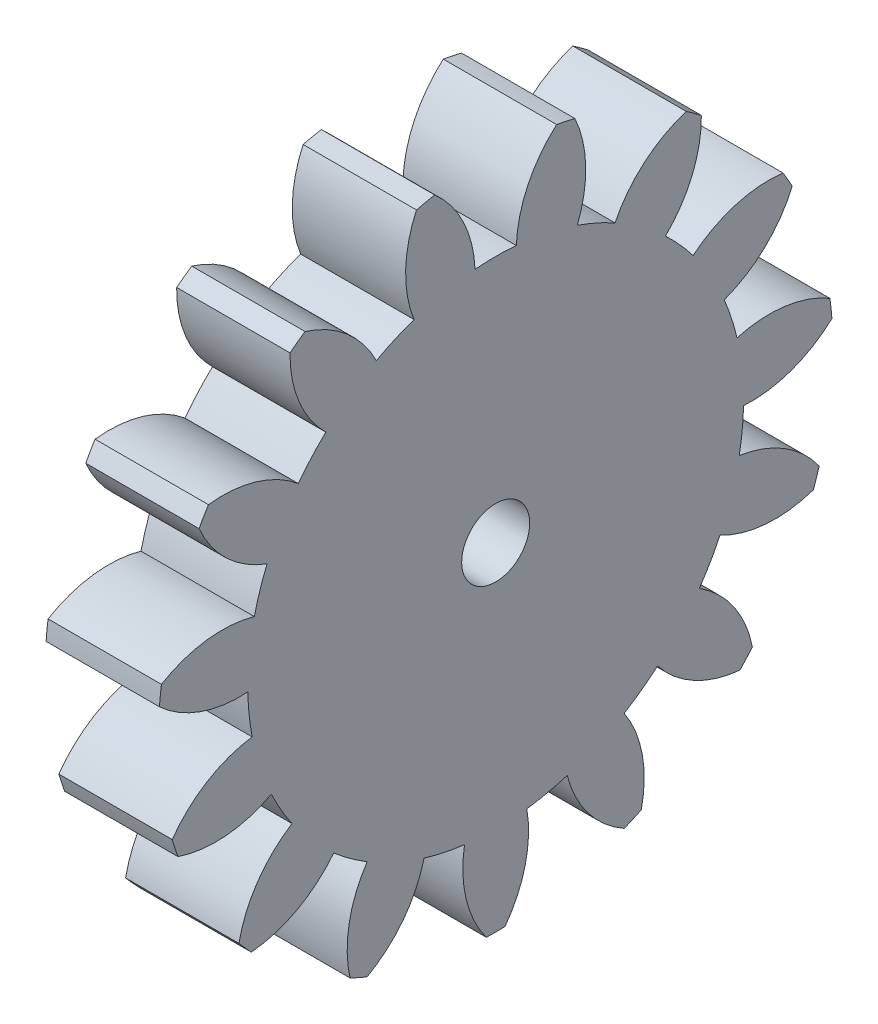
SolidWorks part; units mm, degrees
ref_plane "Plane1" through (0, 0, 0) normal (0, 0, 1) x (1, 0, 0)
ref_plane "Plane2" through (0, 0, 0) normal (0, 1, 0) x (1, 0, 0)
ref_plane "Plane3" through (0, 0, 0) normal (1, 0, 0) x (0, 0, -1)
sketch "HoldingSke" plane through (0, 0, 0) normal (0, 1, 0) x (1, 0, 0)
  line L0 (0, 0) -> (0.552, -0.1479)
  line L1 (-15, 0) -> (100, 0) construction
  line L2 (0, 0) -> (-2.1039, 2.3779)
  line L3 (0, 0) -> (-11.863, 4.5341)
  line L4 (0, 0) -> (8.3417, 2.2352)
  line L5 (0, 0) -> (-46.8476, -17.4728)
  line L6 (0, 0) -> (-4.1448, -2.7965)
  line L7 (-2.1039, 2.3779) -> (8.6586, 51.2059)
  line L8 (-76.2, 54.61) -> (-75.7, 54.61)
  line L9 (-71.009, 38.7566) -> (-53.1078, 45.2721)
  line L10 (-76.2, 71.12) -> (104.1128, 71.12)
  line L11 (0, 0) -> (-5, 0)
  line L12 (-76.2, 101.6) -> (-76.147, 101.6)
  line L13 (24.9733, 27.94) -> (52.9518, 28.4284)
  line L14 (24.9733, 27.94) -> (24.9743, 27.94)
  line L15 (24.9733, 27.94) -> (100.4006, 29.5858)
  line L16 (-63.627, -1.75) -> (-12.827, -1.75)
  circle A0 centre (0, 0) radius 1.5
  circle A1 centre (0, 0) radius 10.9365
  circle A2 centre (0, 0) radius 37.5
  circle A3 centre (0, 0) radius 1.5
  dimension "MHD" = 21.873
  dimension "Hub_dia" = 75
  dimension "Bore" = 3
  dimension "MBD" = 3
  dimension "Overall_len" = 50
  dimension "Thickness" = 5
  dimension "OAL" = 50.0001
  dimension "T_dim" = 0.5
  dimension "Ap" = 20
  dimension "H" = 19.05
  dimension "Pitch_radius" = 180.3128
  dimension "Width" = 5
  dimension "Addendum_fac" = 1
  dimension "Dedendum_fac" = 1.25
  dimension "Clearance_fac" = 0.25
  dimension "Dedendum_add" = 0.001
sketch "BasProSke" plane through (0, 0, 0) normal (0, 1, 0) x (1, 0, 0)
  line L0 (-10, 0) -> (60, 0) construction
  line L1 (0, 0) -> (0, 14.875)
  line L2 (0, 0) -> (5, 0)
  line L3 (5, 0) -> (5, 14.875)
  line L4 (5, 14.875) -> (0, 14.875)
  dimension "Thickness" = 5
revolve "Base-Revolve" add sketch "BasProSke" angle 360 about L0
sketch "TooCutSke" plane through (0, 0, 0) normal (1, 0, 0) x (0, 0, -1)
  line L1 (0, 0) -> (0, 107) construction
  line L2 (0, 0) -> (-1.4646, 13.043) construction
  line L3 (0, 0) -> (-5.4317, 25.5541) construction
  line L4 (-1.4646, 13.043) -> (-2.7158, 12.7771) construction
  arc A0 (0.9106, 10.8985) -> (-0.9106, 10.8985) centre (0, 0) ccw
  arc A1 (2.7141, 14.6511) -> (-2.7141, 14.6511) centre (0, 0) ccw
  circle A2 centre (0, 0) radius 13.125 construction
  circle A3 centre (0, 0) radius 12.3335 construction
  arc A4 (-0.9106, 10.8985) -> (-2.7141, 14.6511) centre (-6.1563, 10.6871) ccw
  arc A5 (2.7141, 14.6511) -> (0.9106, 10.8985) centre (6.1563, 10.6871) ccw
  dimension "Root_dia" = 21.873
  dimension "Flank_rad" = 5.25
extrude "ToothCut" cut sketch "TooCutSke" along normal through all
fillet "Breaks" [suppressed] radius 0.035
fillet "RootFillets" [suppressed] radius 0.4385
pattern_circular "TeethCuts" count 15 every 24 about axis through (-10, 0, 0) along (1, 0, 0) of "ToothCut", "RootFillets", "Breaks"
sketch "HubNeaOneSke" plane through (0, 0, 0) normal (-1, 0, 0) x (0, 0, 1)
  circle A0 centre (0, 0) radius 10.9365
  dimension "Diameter" = 21.873
extrude "HubNearOne" [suppressed] add sketch "HubNeaOneSke" along normal blind 45.0001
sketch "HubNeaBotSke" plane through (0, 0, 0) normal (-1, 0, 0) x (0, 0, 1)
  circle A0 centre (0, 0) radius 10.9365
  dimension "Diameter" = 21.873
extrude "HubNearBoth" [suppressed] add sketch "HubNeaBotSke" along normal blind 22.5
ref_plane "FarPln" through (5, 0, 0) normal (1, 0, 0) x (0, 0, -1)
sketch "HubFarSke" plane through (5, 0, 0) normal (1, 0, 0) x (0, 0, -1)
  circle A0 centre (0, 0) radius 10.9365
  dimension "Diameter" = 21.873
extrude "HubFar" [suppressed] add sketch "HubFarSke" along normal blind 22.5
sketch "BorSke" plane through (0, 0, 0) normal (1, 0, 0) x (0, 0, -1)
  circle A0 centre (0, 0) radius 1.5
  dimension "Diameter" = 3
extrude "Bore" cut sketch "BorSke" along normal mid plane 100.0001
sketch "KeySke" plane through (0, 0, 0) normal (1, 0, 0) x (0, 0, -1)
  line L0 (-0.6, 0) -> (-0.6, 2)
  line L1 (-0.6, 2) -> (0.6, 2)
  line L2 (0.6, 2) -> (0.6, 0)
  line L3 (0, 0) -> (0, 34) construction
  line L4 (-0.6, 0) -> (0.6, 0)
  dimension "Offset" = 2
  dimension "Width" = 1.2
extrude "Keyway" [suppressed] cut sketch "KeySke" along normal mid plane 100.0001
pattern_circular "Keyway2" [suppressed] count 2 every 90 about axis through (-10, 0, 0) along (1, 0, 0)
equation "' \"Module@HoldingSke\" = 6.35"
equation "' \"Num_teeth@HoldingSke\" = 12"
equation "' \"Ap@HoldingSke\" =  20"
equation "' \"Ap@HoldingSke\" = 20"
equation "' \"Width@HoldingSke\" = 0.5 * 25.4"
equation "' \"Hub_dia@HoldingSke\"= 1 * 25.4"
equation "' \"Hub_dia@HoldingSke\" = 1 * 25.4"
equation "' \"Overall_len@HoldingSke\" = 1.0 * 25.4"
equation "' \"Bore@HoldingSke\" = 0.75 * 25.4"
equation "' \"T_dim@HoldingSke\" = 0.1 * 25.4"
equation "' \"Width@KeySke\" = 0.25 * 25.4"
equation "' \"Show_teeth@HoldingSke\" = 13"
equation "' \"Backlash@HoldingSke\" = 0.009 * 25.4"
equation "' \"Addendum_fac@HoldingSke\" = 1.0"
equation "' \"Dedendum_fac@HoldingSke\" = 1.25"
equation "' \"Dedendum_add@HoldingSke\" = 0.00005 * 25.4"
equation "' \"Clearance_fac@HoldingSke\" = 0.25"
equation "\"Pitch@HoldingSke\" = 1 / \"Module@HoldingSke\""
equation "\"Overcut_dia@TooCutSke\" = (\"Num_teeth@HoldingSke\" + 2 * \"Addendum_fac@HoldingSke\") / \"Pitch@HoldingSke\" + 0.002 * 25.4"
equation "\"Pitch_dia@TooCutSke\" = \"Num_teeth@HoldingSke\" / \"Pitch@HoldingSke\""
equation "\"Base_dia@TooCutSke\" = \"Num_teeth@HoldingSke\" / \"Pitch@HoldingSke\" * cos((\"Ap@HoldingSke\"  * 3.14159265 / 180))"
equation "\"Root_dia@TooCutSke\" = (\"Num_teeth@HoldingSke\" + 2) / \"Pitch@HoldingSke\" - 2 * (\"Addendum_fac@HoldingSke\" + \"Dedendum_fac@HoldingSke\") / \"Pitch@HoldingSke\" - \"Dedendum_add@HoldingSke\" * 2"
equation "\"Half_ang@TooCutSke\" = 180 / \"Num_teeth@HoldingSke\""
equation "\"Half_CT@TooCutSke\" = \"Num_teeth@HoldingSke\" / \"Pitch@HoldingSke\" * sin((3.14159265 / 2 / \"Num_teeth@HoldingSke\")) / 2 - 7 * \"Backlash@HoldingSke\" / 4"
equation "\"Flank_rad@TooCutSke\" = \"Num_teeth@HoldingSke\" / \"Pitch@HoldingSke\" / 5"
equation "\"Radius@RootFillets\" = \"Clearance_fac@HoldingSke\" / \"Pitch@HoldingSke\" + \"Dedendum_add@HoldingSke\""
equation "\"Break_rad@Breaks\" = 0.02 / \"Pitch@HoldingSke\""
equation "\"Thickness@HoldingSke\" = \"Width@HoldingSke\""
equation "\"OAL@HoldingSke\" = \"Thickness@HoldingSke\""
equation "\"MHD@HoldingSke\" = (\"Num_teeth@HoldingSke\" + 2) / \"Pitch@HoldingSke\" - 2 * (\"Addendum_fac@HoldingSke\" + \"Dedendum_fac@HoldingSke\")  / \"Pitch@HoldingSke\" - \"Dedendum_add@HoldingSke\" * 2"
equation "\"MBD@HoldingSke\" = (\"Num_teeth@HoldingSke\" + 2) / \"Pitch@HoldingSke\" - 2 * (\"Addendum_fac@HoldingSke\" + \"Dedendum_fac@HoldingSke\")  / \"Pitch@HoldingSke\" - \"Dedendum_add@HoldingSke\" * 2 - 0.002 * 25.4"
equation "\"MHD@HoldingSke\" = ((sgn( \"MHD@HoldingSke\" - \"Hub_dia@HoldingSke\" )-1)*( \"MHD@HoldingSke\" - \"Hub_dia@HoldingSke\" ))/-2+ \"Hub_dia@HoldingSke\""
equation "\"MBD@HoldingSke\" = ((sgn( \"MBD@HoldingSke\" - \"Bore@HoldingSke\" )-1)*( \"MBD@HoldingSke\" - \"Bore@HoldingSke\" ))/-2+ \"Bore@HoldingSke\""
equation "\"OAL@HoldingSke\" = ((sgn( \"OAL@HoldingSke\" - \"Overall_len@HoldingSke\" )+1)*( \"OAL@HoldingSke\" - \"Overall_len@HoldingSke\" ))/2 + \"Overall_len@HoldingSke\" + 0.000002 * 25.4"
equation "\"Num_teeth@TeethCuts\" = int( \"Show_teeth@HoldingSke\" ) + 1"
equation "\"Num_teeth@TeethCuts\" = ((sgn( \"Num_teeth@TeethCuts\" - \"Num_teeth@HoldingSke\" )-1)*( \"Num_teeth@TeethCuts\" - \"Num_teeth@HoldingSke\" ))/-2+ \"Num_teeth@HoldingSke\""
equation "\"Num_teeth@TeethCuts\" = ((sgn( \"Num_teeth@TeethCuts\" - 2.0)+1)*( \"Num_teeth@TeethCuts\" - 2.0))/2 +2.0"
equation "\"Angle@TeethCuts\" = 360.0 / \"Num_teeth@HoldingSke\""
equation "\"Diameter@BasProSke\" = (\"Num_teeth@HoldingSke\" + 2 * \"Addendum_fac@HoldingSke\") / \"Pitch@HoldingSke\""
equation "\"Thickness@BasProSke\"  = \"Thickness@HoldingSke\""
equation "' \"Fillet_rad@BasProSke\" =  \"Thickness@HoldingSke\" * 0.05"
equation "' \"Fillet_rad@BasProSke\" = \"Thickness@HoldingSke\" * 0.05"
equation "\"MHD@HoldingSke\" = ((sgn( \"MHD@HoldingSke\" - \"Root_dia@TooCutSke\" )-1)*( \"MHD@HoldingSke\" - \"Root_dia@TooCutSke\" ))/-2+ \"Root_dia@TooCutSke\""
equation "\"Diameter@HubNeaOneSke\" = \"MHD@HoldingSke\""
equation "\"Length@HubNearOne\" = \"OAL@HoldingSke\" - \"Thickness@BasProSke\""
equation "\"Diameter@HubNeaBotSke\" = \"MHD@HoldingSke\""
equation "\"Length@HubNearBoth\" = ( \"OAL@HoldingSke\" - \"Thickness@BasProSke\" ) / 2.0"
equation "\"Thickness@FarPln\" = \"Thickness@BasProSke\""
equation "\"Diameter@HubFarSke\" = \"MHD@HoldingSke\""
equation "\"Length@HubFar\" = ( \"OAL@HoldingSke\" - \"Thickness@BasProSke\" ) / 2.0"
equation "\"Diameter@BorSke\" = \"MBD@HoldingSke\""
equation "\"D1@Bore\" = \"OAL@HoldingSke\" * 2.0"
equation "\"D1@Keyway\" = \"OAL@HoldingSke\" * 2.0"
equation "\"Offset@KeySke\" = \"T_dim@HoldingSke\" + \"MBD@HoldingSke\" / 2.0"
